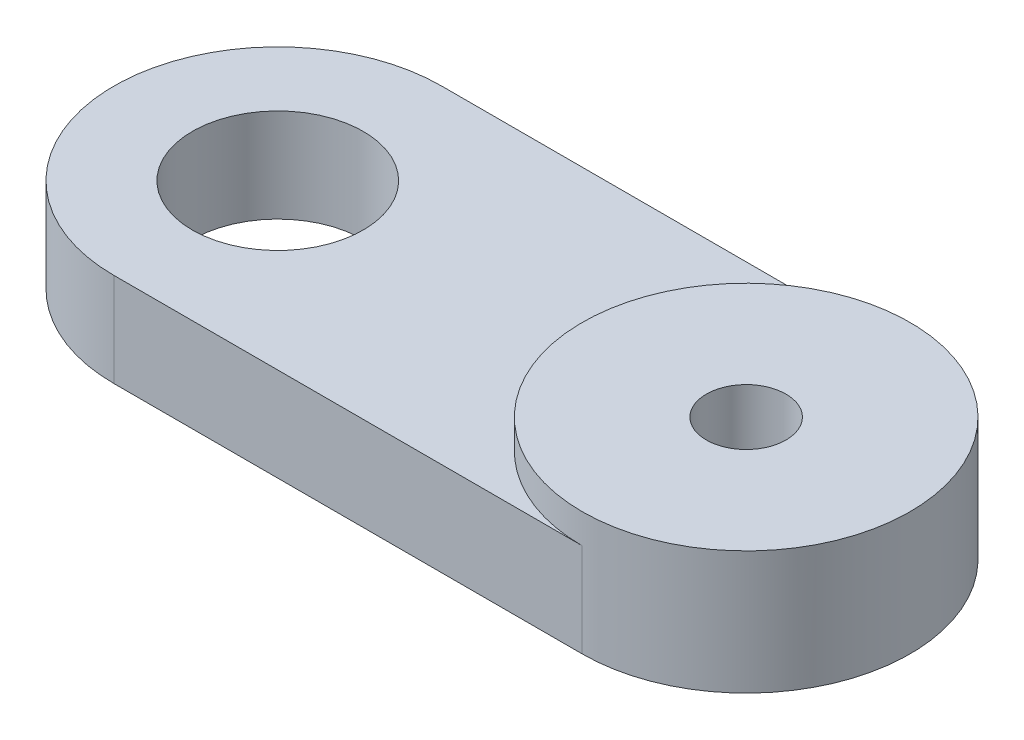
SolidWorks part; units mm, degrees
material "Copper"
ref_plane "Front Plane" through (0, 0, 0) normal (0, 0, 1) x (1, 0, 0)
ref_plane "Top Plane" through (0, 0, 0) normal (0, 1, 0) x (1, 0, 0)
ref_plane "Right Plane" through (0, 0, 0) normal (1, 0, 0) x (0, 0, -1)
sketch "Sketch1" plane through (0, 0, 0) normal (0, 1, 0) x (1, 0, 0)
  line L0 (0, 0) -> (12.7, 0) construction
  line L1 (0, 4.445) -> (12.7, 4.445)
  line L2 (0, -4.445) -> (12.7, -4.445)
  circle A0 centre (0, 0) radius 2.3177
  circle A1 centre (0, 0) radius 4.445
  circle A2 centre (12.7, 0) radius 4.445
  circle A3 centre (12.7, 0) radius 1.0795
  dimension "D1" = 4.6355
  dimension "D2" = 8.89
  dimension "D3" = 2.159
  dimension "D4" = 8.89
  dimension "D5" = 12.7
extrude "Base Extrude" add sketch "Sketch1" along normal blind 2.54
sketch "Sketch2" plane through (0, 2.54, 0) normal (0, 1, 0) x (1, 0, 0)
  circle A0 centre (12.7, 0) radius 1.0795 construction
  circle A1 centre (12.7, 0) radius 1.0795
  circle A2 centre (12.7, 0) radius 4.445
  arc A3 (12.7, -4.445) -> (12.7, 4.445) centre (12.7, 0) ccw construction
extrude "Servo Extrude" add sketch "Sketch2" along normal blind 0.8
sketch "Sketch3" plane through (0, 0, 0) normal (0, -1, 0) x (1, 0, 0)
  circle A0 centre (12.7, 0) radius 1.0795 construction
  circle A1 centre (12.7, 0) radius 1.0795
  circle A2 centre (12.7, 0) radius 2.794
  dimension "D1" = 5.588
extrude "Servo Mount Cut" cut sketch "Sketch3" against normal offset from surface (1.816 mm away) 1.524 up to face at (12.7, 3.34, 4.445)
